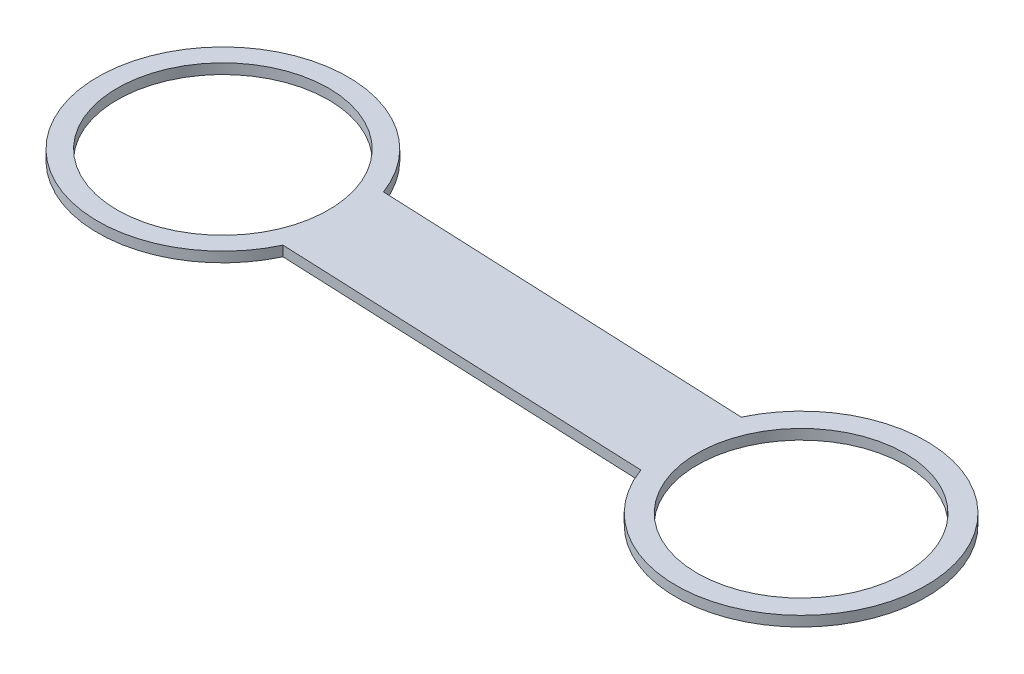
SolidWorks part; units mm, degrees
ref_plane "Front Plane" through (0, 0, 0) normal (0, 0, 1) x (1, 0, 0)
ref_plane "Top Plane" through (0, 0, 0) normal (0, 1, 0) x (1, 0, 0)
ref_plane "Right Plane" through (0, 0, 0) normal (1, 0, 0) x (0, 0, -1)
sketch "Sketch1" plane through (0, 0, 0) normal (0, 1, 0) x (1, 0, 0)
  line L1 (34.7245, 12.7755) -> (145.341, 8)
  line L2 (33.4954, -15.7181) -> (144.0331, -20.4012)
  circle A0 centre (0, 0) radius 31.242
  arc A1 (34.7245, 12.7755) -> (33.4954, -15.7181) centre (0, 0) ccw
  circle A2 centre (178.811, -7.7721) radius 30.734
  arc A3 (144.0331, -20.4012) -> (145.341, 8) centre (178.811, -7.7721) ccw
extrude "Boss-Extrude1" add sketch "Sketch1" along normal blind 3
